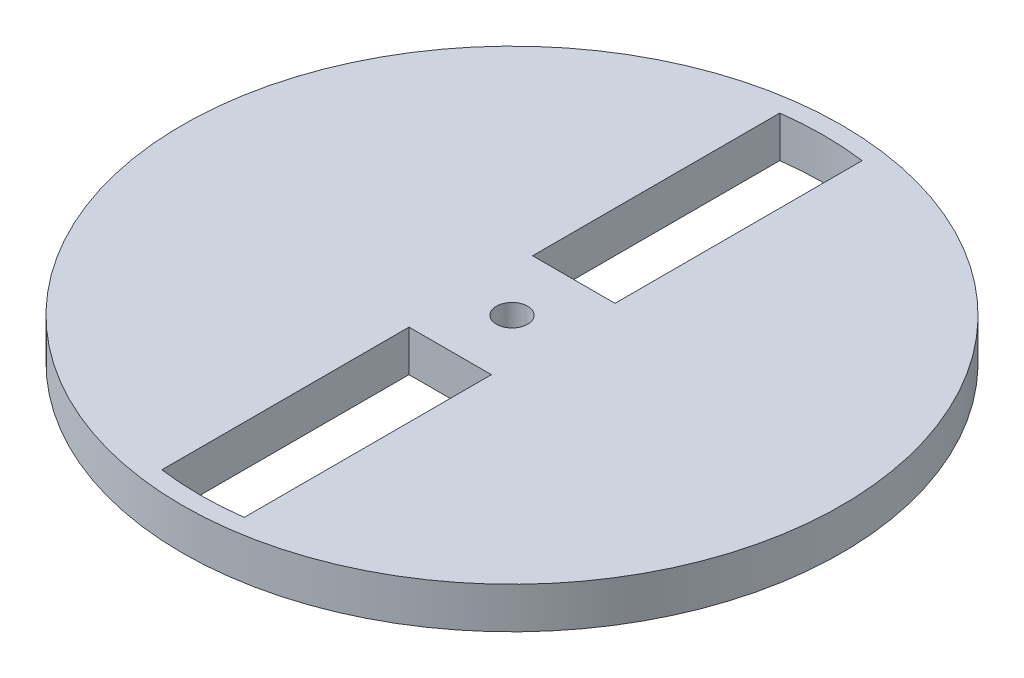
SolidWorks part; units mm, degrees
ref_plane "Front Plane" through (0, 0, 0) normal (0, 0, 1) x (1, 0, 0)
ref_plane "Top Plane" through (0, 0, 0) normal (0, 1, 0) x (1, 0, 0)
ref_plane "Right Plane" through (0, 0, 0) normal (1, 0, 0) x (0, 0, -1)
sketch "Sketch1" plane through (0, 0, 0) normal (0, 1, 0) x (1, 0, 0)
  line L0 (0, 23.9904) -> (0, -26.2934) construction
  line L1 (-10.7087, 0) -> (16.8819, 0) construction
  line L2 (-2.5, 3.75) -> (2.5, 3.75)
  line L3 (-2.5, 3.75) -> (-2.5, 18.75)
  line L5 (2.5, 3.75) -> (2.5, 18.75)
  line L6 (-2.5, 3.75) -> (2.5, 18.75) construction
  line L7 (-2.5, 18.75) -> (2.5, 3.75) construction
  line L12 (2.5, -3.75) -> (2.5, -18.75)
  line L13 (-2.5, -3.75) -> (2.5, -3.75)
  line L14 (-2.5, -3.75) -> (-2.5, -18.75)
  circle A0 centre (0, 0) radius 20
  circle A1 centre (0, 0) radius 0.95
  arc A3 (-2.5, 18.75) -> (2.5, 18.75) centre (0, 0) cw
  arc A4 (-2.5, -18.75) -> (2.5, -18.75) centre (0, 0) ccw
  point P6 (0, 11.25)
  dimension "D1" = 1.9
  dimension "D2" = 40
  dimension "D3" = 5
  dimension "D4" = 15
  dimension "D5" = 3.75
extrude "Boss-Extrude1" add sketch "Sketch1" along normal blind 2.5
